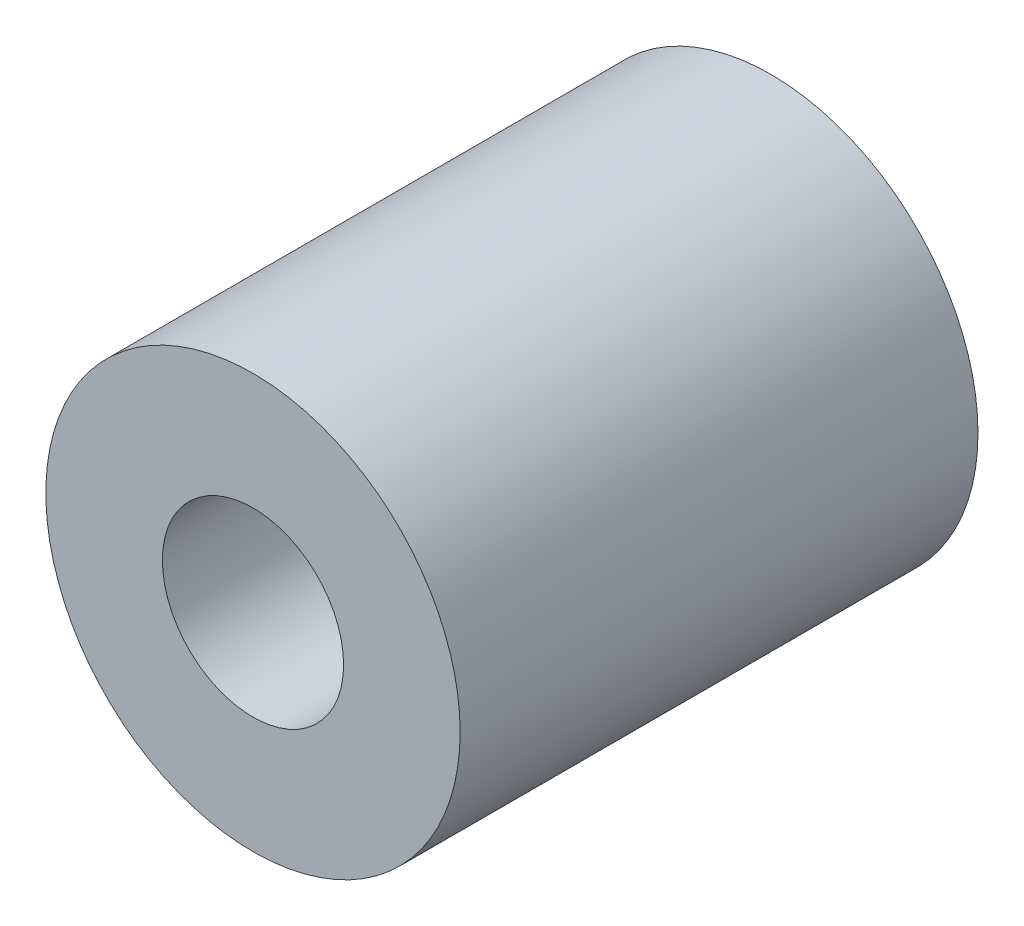
SolidWorks part; units mm, degrees
ref_plane "Front Plane" through (0, 0, 0) normal (0, 0, 1) x (1, 0, 0)
ref_plane "Top Plane" through (0, 0, 0) normal (0, 1, 0) x (1, 0, 0)
ref_plane "Right Plane" through (0, 0, 0) normal (1, 0, 0) x (0, 0, -1)
sketch "Sketch1" plane through (0, 0, 0) normal (0, 0, 1) x (1, 0, 0)
  circle A0 centre (0, 0) radius 4
  circle A1 centre (0, 0) radius 1.75
  dimension "D1" = 8
  dimension "D2" = 3.5
extrude "Boss-Extrude1" add sketch "Sketch1" along normal blind 10
